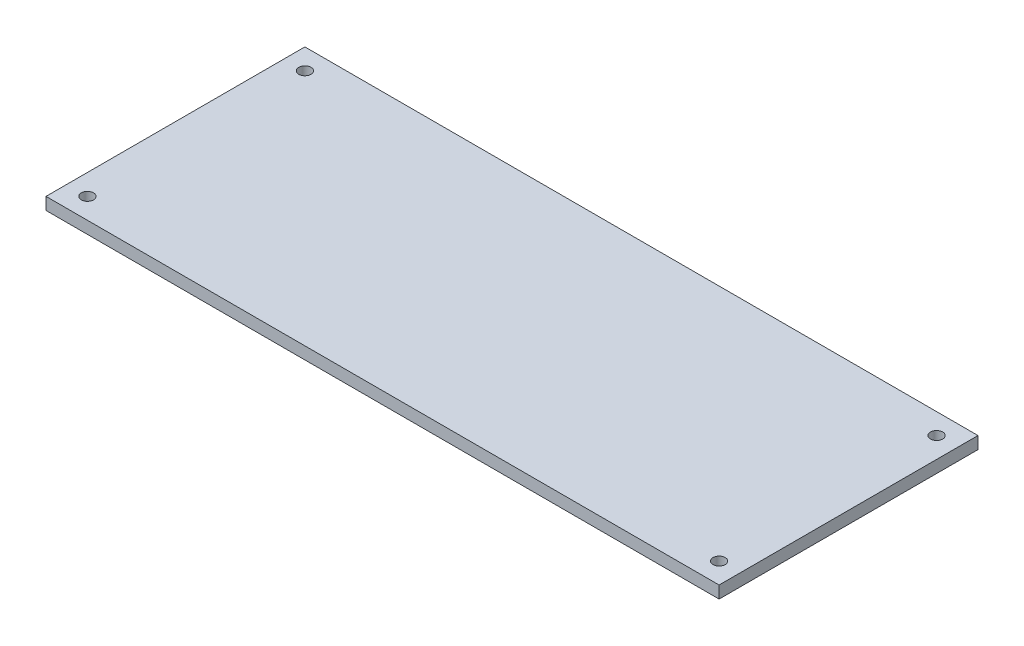
SolidWorks part; units mm, degrees
material "Thornel VCB-20 Carbon Cloth"
ref_plane "Front Plane" through (0, 0, 0) normal (0, 0, 1) x (1, 0, 0)
ref_plane "Top Plane" through (0, 0, 0) normal (0, 1, 0) x (1, 0, 0)
ref_plane "Right Plane" through (0, 0, 0) normal (1, 0, 0) x (0, 0, -1)
sketch "Sketch1" plane through (0, 0, 0) normal (0, 1, 0) x (1, 0, 0)
  line L1 (-82.55, -31.75) -> (82.55, -31.75)
  line L2 (-82.55, -31.75) -> (-82.55, 31.75)
  line L3 (-82.55, 31.75) -> (82.55, 31.75)
  line L4 (82.55, -31.75) -> (82.55, 31.75)
  dimension "D1" = 63.5
  dimension "D2" = 165.1
  dimension "D3" = 31.75
  dimension "D4" = 82.55
extrude "Boss-Extrude1" add sketch "Sketch1" along normal blind 3
sketch "Sketch2" plane through (0, 3, 0) normal (0, 1, 0) x (1, 0, 0)
  line L0 (-82.55, 31.75) -> (-82.55, -31.75) construction
  line L1 (82.55, -31.75) -> (82.55, 31.75) construction
  line L2 (82.55, 31.75) -> (-82.55, 31.75) construction
  line L3 (-82.55, -31.75) -> (82.55, -31.75) construction
  circle A0 centre (-77.47, 26.67) radius 1.5
  circle A1 centre (-77.47, -26.67) radius 1.5
  circle A2 centre (77.47, 26.67) radius 1.5
  circle A3 centre (77.47, -26.67) radius 1.5
  dimension "D1" = 3
  dimension "D2" = 3
  dimension "D3" = 3
  dimension "D4" = 3
  dimension "D5" = 5.08
  dimension "D6" = 5.08
  dimension "D7" = 5.08
  dimension "D8" = 5.08
  dimension "D9" = 5.08
  dimension "D10" = 5.08
  dimension "D11" = 5.08
  dimension "D12" = 5.08
extrude "Cut-Extrude1" cut sketch "Sketch2" against normal up to next
